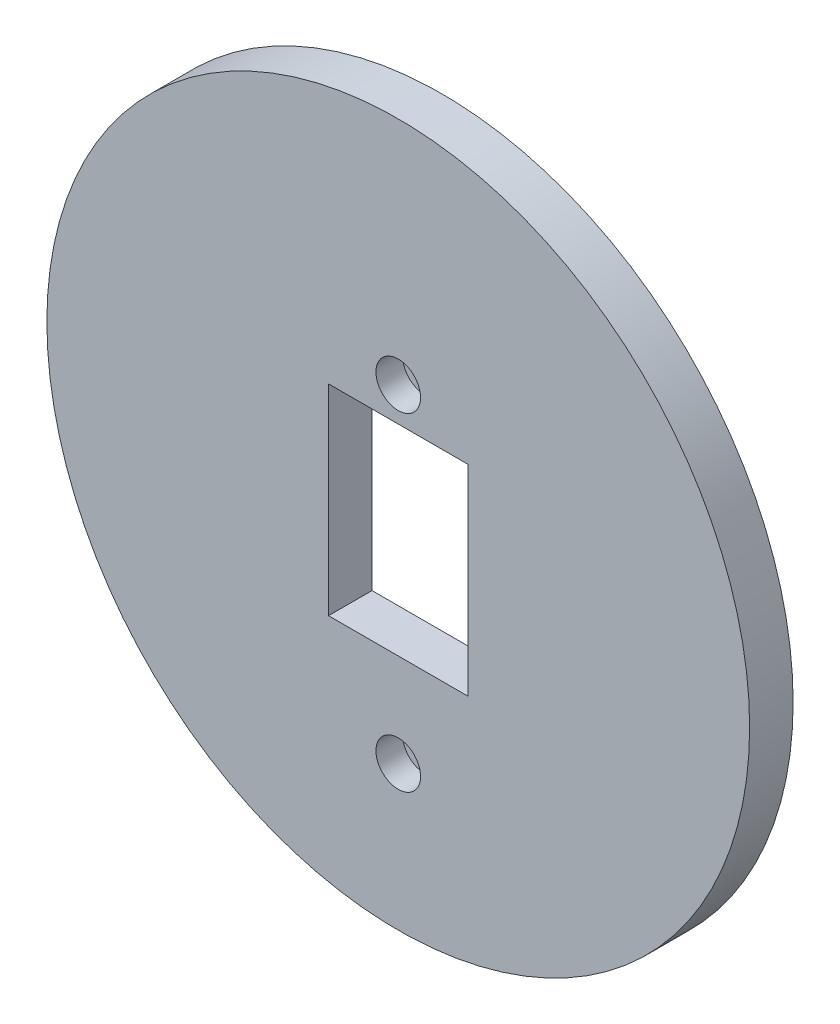
SolidWorks part; units mm, degrees
ref_plane "Alzado" through (0, 0, 0) normal (0, 0, 1) x (1, 0, 0)
ref_plane "Planta" through (0, 0, 0) normal (0, 1, 0) x (1, 0, 0)
ref_plane "Vista lateral" through (0, 0, 0) normal (1, 0, 0) x (0, 0, -1)
sketch "Croquis1" plane through (0, 0, 0) normal (0, 0, 1) x (1, 0, 0)
  circle A0 centre (-51.2357, 9.7866) radius 31.5
  dimension "D1" = 63
extrude "Saliente-Extruir1" add sketch "Croquis1" along normal blind 2.4
sketch "Croquis2" plane through (0, 0, 2.4) normal (0, 0, 1) x (1, 0, 0)
  line L0 (-51.2357, 9.7866) -> (-51.2357, -21.7134) construction
  line L1 (-51.2357, 9.7866) -> (-51.2357, 15.7866) construction
  line L2 (-51.2357, 15.7866) -> (-51.2357, 20.7866) construction
  line L3 (-51.2357, 20.7866) -> (-51.2357, 22.5866) construction
  line L4 (-51.2357, 22.5866) -> (-57.4857, 22.5866) construction
  line L6 (-57.4857, 22.5866) -> (-44.9857, 22.5866)
  line L7 (-57.4857, 22.5866) -> (-57.4857, -10.4134)
  line L8 (-57.4857, -10.4134) -> (-44.9857, -10.4134)
  line L9 (-44.9857, 22.5866) -> (-44.9857, -10.4134)
  line L14 (-59.2857, 24.3866) -> (-43.1857, 24.3866)
  line L15 (-59.2857, 24.3866) -> (-59.2857, -12.2134)
  line L16 (-59.2857, -12.2134) -> (-43.1857, -12.2134)
  line L17 (-43.1857, 24.3866) -> (-43.1857, -12.2134)
  circle A0 centre (-51.2357, 9.7866) radius 31.5 construction
  dimension "D1" = 6
  dimension "D2" = 5
  dimension "D3" = 1.8
  dimension "D4" = 6.25
  dimension "D5" = 12.5
  dimension "D6" = 33
  dimension "D7" = 1.8
  dimension "D8" = 1.8
  dimension "D9" = 1.8
  dimension "D10" = 1.8
extrude "Saliente-Extruir2" add sketch "Croquis2" along normal blind 22.5
sketch "Croquis5" plane through (0, 0, 2.4) normal (0, 0, 1) x (1, 0, 0)
  line L1 (-59.2857, 24.3866) -> (-43.1857, 24.3866)
  line L2 (-59.2857, 24.3866) -> (-59.2857, -12.2134)
  line L3 (-59.2857, -12.2134) -> (-43.1857, -12.2134)
  line L4 (-43.1857, 24.3866) -> (-43.1857, -12.2134)
extrude "Cortar-Extruir2" cut sketch "Croquis5" against normal blind 9
sketch "Croquis6" plane through (0, 0, 0) normal (0, 0, -1) x (-1, 0, 0)
  line L6 (51.2357, 9.7866) -> (73.5095, 32.0605) construction
  line L7 (73.5095, 32.0605) -> (73.5095, -12.4873) construction
  line L8 (73.5095, -12.4873) -> (28.9618, 32.0605) construction
  line L9 (28.9618, 32.0605) -> (28.9618, -12.4873) construction
  line L10 (28.9618, -12.4873) -> (51.2357, 9.7866) construction
  line L11 (51.2357, 24.3866) -> (53.2357, 24.3866)
  line L12 (43.1857, 24.3866) -> (59.2857, 24.3866) construction
  line L13 (53.2357, 24.3866) -> (53.2357, 44.3866)
  line L14 (53.2357, 44.3866) -> (49.2357, 44.3866)
  line L15 (49.2357, 44.3866) -> (49.2357, 24.3866)
  line L16 (49.2357, 24.3866) -> (51.2357, 24.3866)
  circle A0 centre (51.2357, 9.7866) radius 31.5 construction
  circle A1 centre (34.6187, 26.4036) radius 1.5
  circle A2 centre (67.8527, 26.4036) radius 1.5
  circle A3 centre (67.8527, -6.8304) radius 1.5
  circle A4 centre (34.6187, -6.8304) radius 1.5
  dimension "D3" = 8
  dimension "D1" = 20
  dimension "D2" = 4
extrude "Cortar-Extruir3" cut sketch "Croquis6" against normal blind 2.4
sketch "Croquis7" plane through (0, 22.5866, 0) normal (0, -1, 0) x (1, 0, 0)
  line L0 (-57.4857, 24.9) -> (-57.4857, 2.4) construction
  line L1 (-57.4857, 17.9) -> (-44.9857, 17.9)
  line L2 (-57.4857, 17.9) -> (-57.4857, 8.9)
  line L3 (-57.4857, 8.9) -> (-44.9857, 8.9)
  line L4 (-44.9857, 17.9) -> (-44.9857, 8.9)
  line L5 (-44.9857, 24.9) -> (-44.9857, 2.4) construction
  line L6 (-44.9857, 24.9) -> (-57.4857, 24.9) construction
  dimension "D1" = 9
  dimension "D2" = 7
extrude "Saliente-Extruir3" add sketch "Croquis7" along normal up to vertex (33 mm away)
sketch "Croquis8" plane through (0, 0, 17.9) normal (0, 0, 1) x (1, 0, 0)
  line L0 (-44.9857, -10.4134) -> (-44.9857, 22.5866) construction
  line L1 (-44.9857, -5.4134) -> (-57.4857, -5.4134)
  line L2 (-44.9857, -5.4134) -> (-44.9857, 17.5866)
  line L4 (-57.4857, -5.4134) -> (-57.4857, 17.5866)
  line L5 (-57.4857, -10.4134) -> (-57.4857, 22.5866) construction
  line L6 (-44.9857, -10.4134) -> (-57.4857, -10.4134) construction
  line L9 (-44.9857, 17.5866) -> (-49.2357, 17.5866)
  line L10 (-49.2357, 17.5866) -> (-49.2357, 19.5866)
  line L11 (-49.2357, 19.5866) -> (-53.2357, 19.5866)
  line L12 (-53.2357, 19.5866) -> (-53.2357, 17.5866)
  line L13 (-53.2357, 17.5866) -> (-57.4857, 17.5866)
  line L14 (-44.9857, 22.5866) -> (-57.4857, 22.5866) construction
  circle A0 centre (-51.2357, -8.4134) radius 1
  circle A1 centre (-51.2357, 20.6366) radius 1
  dimension "D3" = 2
  dimension "D6" = 1.95
  dimension "D1" = 5
  dimension "D2" = 5
  dimension "D4" = 4
  dimension "D5" = 2
extrude "Cortar-Extruir5" cut sketch "Croquis8" against normal blind 9
sketch "Croquis9" plane through (-44.9857, 0, 0) normal (-1, 0, 0) x (0, 0, 1)
  line L0 (8.9, -5.4134) -> (3.9, -10.4134)
  line L1 (8.9, -10.4134) -> (2.4, -10.4134) construction
  line L2 (3.9, -10.4134) -> (8.9, -10.4134)
  line L3 (8.9, -10.4134) -> (8.9, -5.4134)
  line L4 (8.9, 17.5866) -> (3.9, 22.5866)
  line L5 (8.9, 22.5866) -> (2.4, 22.5866) construction
  line L6 (3.9, 22.5866) -> (8.9, 22.5866)
  line L7 (8.9, 22.5866) -> (8.9, 17.5866)
extrude "Saliente-Extruir4" add sketch "Croquis9" along normal up to vertex (12.5 mm away)
sketch "Croquis10" plane through (0, 0, 8.9) normal (0, 0, 1) x (1, 0, 0)
  line L1 (-53.2357, 17.5866) -> (-49.2357, 17.5866)
  line L2 (-53.2357, 17.5866) -> (-53.2357, 19.5866)
  line L3 (-53.2357, 19.5866) -> (-49.2357, 19.5866)
  line L4 (-49.2357, 17.5866) -> (-49.2357, 19.5866)
extrude "Cortar-Extruir6" cut sketch "Croquis10" against normal blind 9
sketch "Croquis11" plane through (0, 0, 24.9) normal (0, 0, 1) x (1, 0, 0)
  line L0 (-57.4857, -10.4134) -> (-44.9857, -10.4134) construction
  line L1 (-57.4857, 17.5866) -> (-44.9857, 17.5866)
  line L2 (-57.4857, 17.5866) -> (-57.4857, -0.4134)
  line L3 (-57.4857, -0.4134) -> (-44.9857, -0.4134)
  line L4 (-44.9857, 17.5866) -> (-44.9857, -0.4134)
  line L5 (-44.9857, 22.5866) -> (-57.4857, 22.5866) construction
  line L6 (-43.1857, -12.2134) -> (-43.1857, 24.3866) construction
  line L7 (-59.2857, 24.3866) -> (-59.2857, -12.2134) construction
  circle A0 centre (-51.2357, 9.7866) radius 31.5
  dimension "D1" = 10
  dimension "D5" = 63
  dimension "D2" = 5
  dimension "D3" = 1.8
  dimension "D4" = 1.8
extrude "Saliente-Extruir5" add sketch "Croquis11" along normal blind 3.9
sketch "Croquis12" plane through (0, 0, 17.9) normal (0, 0, 1) x (1, 0, 0)
  circle A0 centre (-51.2357, 20.6366) radius 1
  circle A1 centre (-51.2357, -8.4134) radius 1
extrude "Cortar-Extruir7" cut sketch "Croquis12" along normal up to vertex
sketch "Croquis13" plane through (0, 0, 28.8) normal (0, 0, 1) x (1, 0, 0)
  circle A0 centre (-51.2357, 20.6366) radius 2
  circle A1 centre (-51.2357, -8.7712) radius 2
extrude "Cortar-Extruir8" cut sketch "Croquis13" against normal blind 2.4
sketch "Croquis14" plane through (0, 0, 0) normal (0, 0, -1) x (-1, 0, 0)
  circle A0 centre (51.2357, 9.7866) radius 31.5
extrude "Cortar-Extruir9" cut sketch "Croquis14" against normal up to vertex (24.9 mm away)
